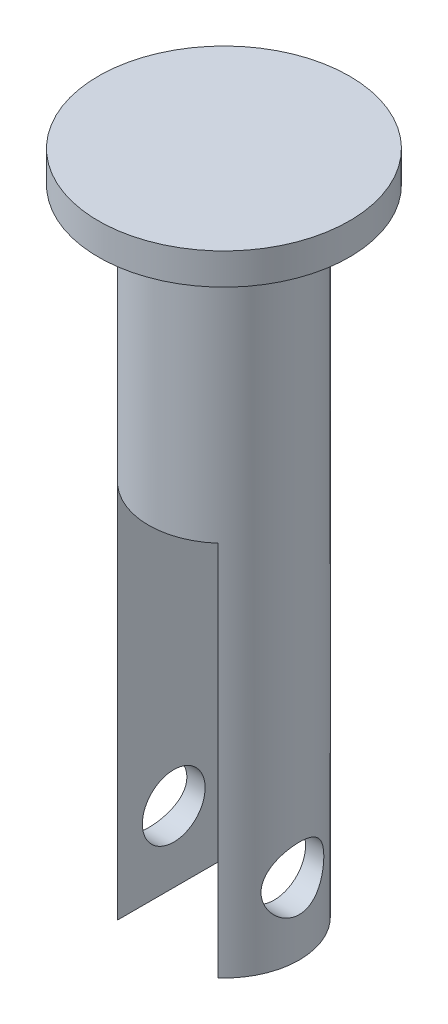
SolidWorks part; units mm, degrees
material "普通碳钢"
ref_plane "前视基准面" through (0, 0, 0) normal (0, 0, 1) x (1, 0, 0)
ref_plane "上视基准面" through (0, 0, 0) normal (0, 1, 0) x (1, 0, 0)
ref_plane "右视基准面" through (0, 0, 0) normal (1, 0, 0) x (0, 0, -1)
sketch "草图1" plane through (0, 0, 0) normal (0, 0, 1) x (1, 0, 0)
  line L0 (-0.4559, 112.0665) -> (19.5441, 112.0665)
  line L1 (19.5441, 112.0665) -> (19.5441, 107.0665)
  line L2 (19.5441, 107.0665) -> (11.5441, 107.0665)
  line L3 (11.5441, 107.0665) -> (11.5441, 6.0665)
  line L4 (11.5441, 6.0665) -> (-0.4559, 6.0665)
  line L7 (-0.4559, 6.0665) -> (-0.4559, 112.0665)
  dimension "D1" = 12
  dimension "D2" = 20
  dimension "D3" = 5
  dimension "D4" = 106
revolve "旋转1" add sketch "草图1" angle 360 about L7
sketch "草图4" plane through (0, 0, 0) normal (0, 0, 1) x (1, 0, 0)
  line L0 (-12.4559, 6.0665) -> (11.5441, 6.0665) construction
  line L1 (-8.4559, 66.0665) -> (7.5441, 66.0665)
  line L2 (-8.4559, 66.0665) -> (-8.4559, -3.9335)
  line L3 (-8.4559, -3.9335) -> (7.5441, -3.9335)
  line L4 (7.5441, 66.0665) -> (7.5441, -3.9335)
  dimension "D1" = 16
  dimension "D2" = 4
  dimension "D3" = 70
  dimension "D4" = 10
extrude "切除-拉伸1" cut sketch "草图4" against normal mid plane 30 contours L3 L4 L1 L2
sketch "草图6" plane through (0, 0, 0) normal (1, 0, 0) x (0, 0, -1)
  circle A0 centre (0, 17.3471) radius 5
  dimension "D1" = 10
extrude "切除-拉伸2" cut sketch "草图6" against normal mid plane 30
sketch "草图7" plane through (0, 0, 0) normal (1, 0, 0) x (0, 0, -1)
  circle A0 centre (0, 17.3471) radius 40
  circle A1 centre (0, 17.3471) radius 5
  dimension "D1" = 80
extrude "凸台-拉伸1" [suppressed] add sketch "草图7" along normal mid plane 10 contours A0
